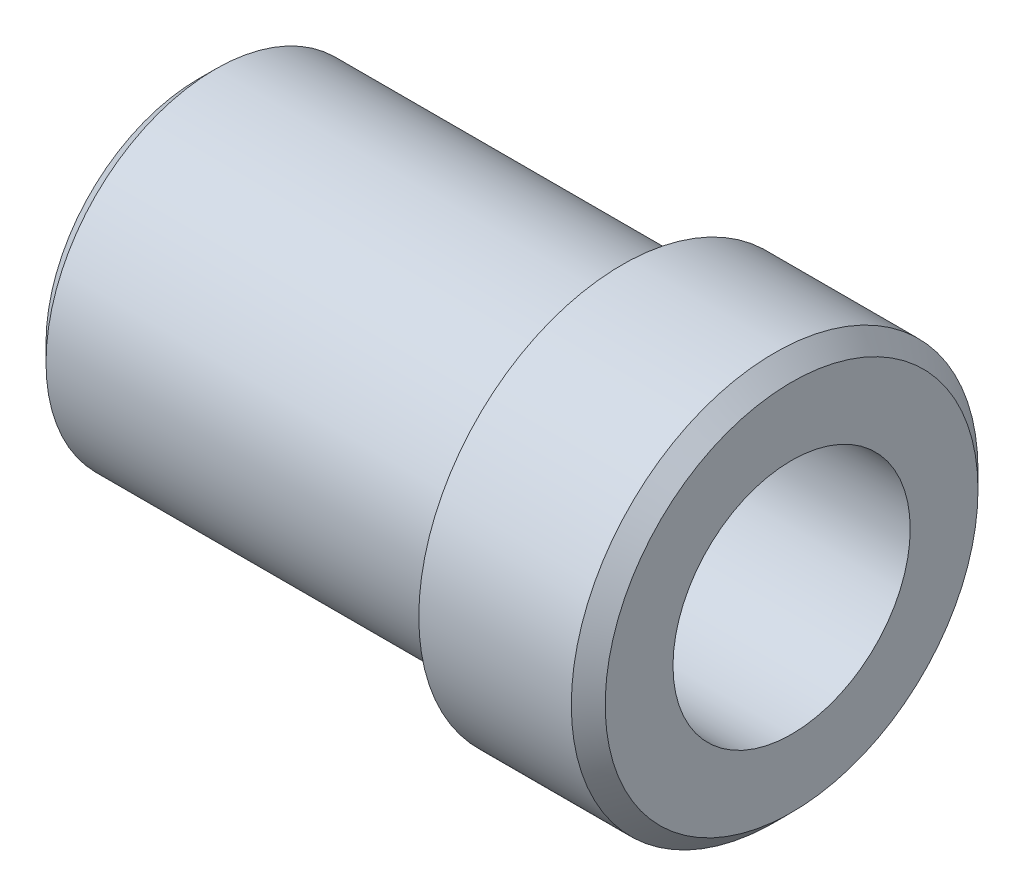
SolidWorks part; units mm, degrees
ref_plane "Front Plane" through (0, 0, 0) normal (0, 0, 1) x (1, 0, 0)
ref_plane "Top Plane" through (0, 0, 0) normal (0, 1, 0) x (1, 0, 0)
ref_plane "Right Plane" through (0, 0, 0) normal (1, 0, 0) x (0, 0, -1)
sketch "Sketch1" plane through (0, 0, 0) normal (0, 0, 1) x (1, 0, 0)
  line L0 (0, 7) -> (0, 12)
  line L1 (-10, 12) -> (-10, 10)
  line L2 (-10, 10) -> (-35, 10)
  line L3 (-35, 10) -> (-35, 7)
  line L4 (-35, 7) -> (0, 7)
  line L5 (-10, 12) -> (0, 12)
  line L6 (0, 0) -> (-56.4202, 0) construction
  dimension "D1" = 35
  dimension "D2" = 10
  dimension "D3" = 7
  dimension "D4" = 10
  dimension "D5" = 12
revolve "Revolve1" add sketch "Sketch1" angle 360 about L6
chamfer "Chamfer1" distance 1 angle 45 2 edges at (0, 0, -12) (-35, 0, -10)
